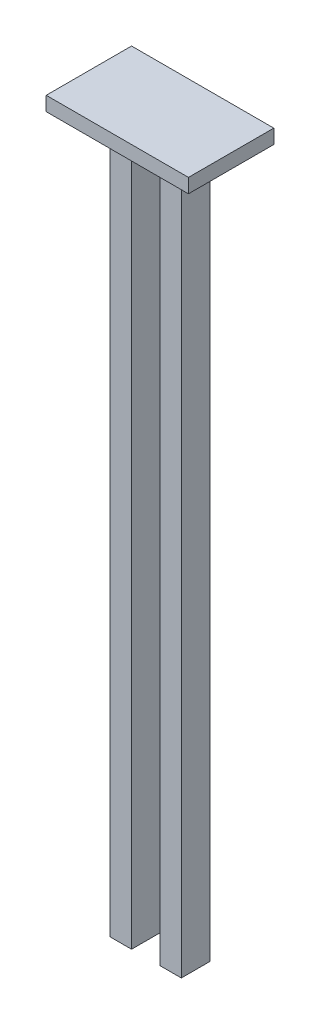
SolidWorks part; units mm, degrees
ref_plane "Front Plane" through (0, 0, 0) normal (0, 0, 1) x (1, 0, 0)
ref_plane "Top Plane" through (0, 0, 0) normal (0, 1, 0) x (1, 0, 0)
ref_plane "Right Plane" through (0, 0, 0) normal (1, 0, 0) x (0, 0, -1)
sketch "Sketch1" plane through (0, 0, 0) normal (0, 1, 0) x (1, 0, 0)
  line L1 (-5, 3) -> (5, 3)
  line L2 (-5, 3) -> (-5, -3)
  line L3 (-5, -3) -> (5, -3)
  line L4 (5, 3) -> (5, -3)
  point P4 (0, -3)
  point P5 (5, 0)
  dimension "D1" = 6
  dimension "D2" = 10
extrude "Boss-Extrude1" add sketch "Sketch1" along normal blind 1
sketch "Sketch2" plane through (0, 0, 0) normal (0, -1, 0) x (1, 0, 0)
  line L1 (-2.5, 1) -> (2.5, 1)
  line L2 (-2.5, 1) -> (-2.5, -1)
  line L3 (-2.5, -1) -> (2.5, -1)
  line L4 (2.5, 1) -> (2.5, -1)
  line L5 (-1, 1) -> (1, 1)
  line L6 (-1, 1) -> (-1, -1)
  line L7 (-1, -1) -> (1, -1)
  line L8 (1, 1) -> (1, -1)
  point P4 (0, -1)
  point P5 (-2.5, 0)
  dimension "D1" = 5
  dimension "D2" = 2
  dimension "D3" = 2
  dimension "D4" = 1
extrude "Boss-Extrude2" add sketch "Sketch2" along normal blind 50 contours L6 L1 L2 L3 | L1 L8 L3 L4
